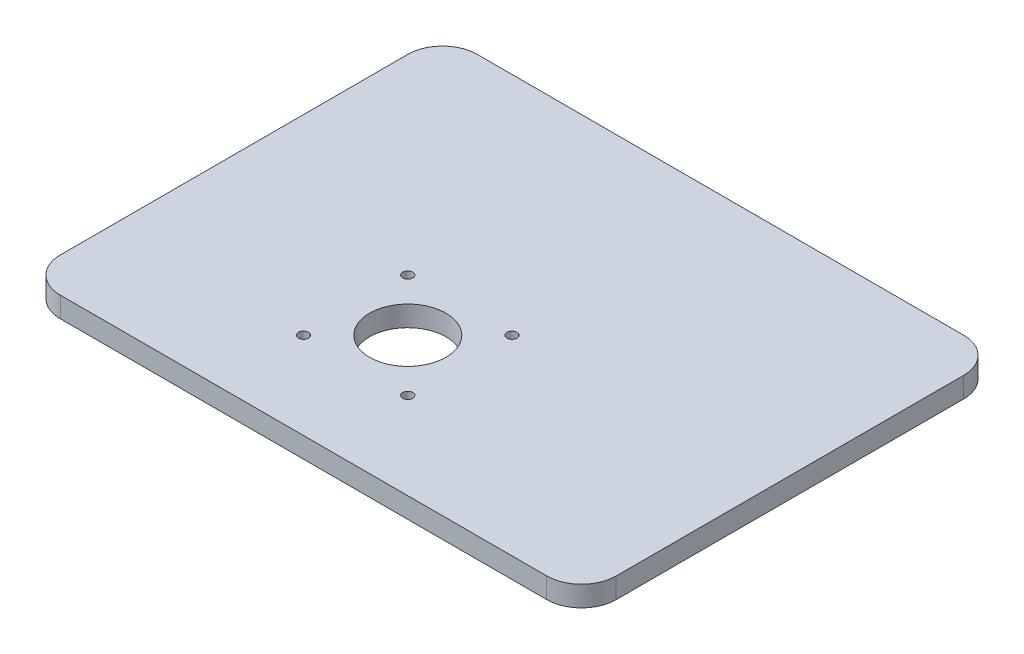
SolidWorks part; units mm, degrees
material "Oak"
ref_plane "Front Plane" through (0, 0, 0) normal (0, 0, 1) x (1, 0, 0)
ref_plane "Top Plane" through (0, 0, 0) normal (0, 1, 0) x (1, 0, 0)
ref_plane "Right Plane" through (0, 0, 0) normal (1, 0, 0) x (0, 0, -1)
sketch "Sketch3" plane through (0, 0, 0) normal (0, 1, 0) x (1, 0, 0)
  line L1 (0, 3.3296) -> (160, 3.3296)
  line L2 (0, 3.3296) -> (0, -116.6704)
  line L3 (0, -116.6704) -> (160, -116.6704)
  line L4 (160, 3.3296) -> (160, -116.6704)
  line L5 (70, -76.6704) -> (85, -76.6704) construction
  line L6 (70, -76.6704) -> (70, -91.6704) construction
  line L7 (70, -91.6704) -> (85, -91.6704) construction
  line L8 (85, -76.6704) -> (85, -91.6704) construction
  line L9 (55, -61.6704) -> (85, -61.6704) construction
  line L10 (55, -61.6704) -> (55, -91.6704) construction
  line L11 (55, -91.6704) -> (85, -91.6704) construction
  line L12 (85, -61.6704) -> (85, -91.6704) construction
  line L13 (55, -61.6704) -> (85, -91.6704) construction
  line L14 (55, -91.6704) -> (85, -61.6704) construction
  circle A0 centre (70, -76.6704) radius 11
  circle A1 centre (55, -61.6704) radius 1.45
  circle A2 centre (85, -61.6704) radius 1.45
  circle A3 centre (85, -91.6704) radius 1.45
  circle A4 centre (55, -91.6704) radius 1.45
  dimension "D5" = 22
  dimension "D8" = 2.9
  dimension "D9" = 2.9
  dimension "D10" = 2.9
  dimension "D11" = 2.9
  dimension "D1" = 160
  dimension "D2" = 120
  dimension "D3" = 80
  dimension "D4" = 70
  dimension "D6" = 15
  dimension "D7" = 15
extrude "Boss-Extrude1" add sketch "Sketch3" along normal blind 5.9
fillet "Fillet1" radius 10 4 edges at (160, 2.95, 116.6704) (160, 2.95, -3.3296) (0, 2.95, -3.3296) (0, 2.95, 116.6704)
